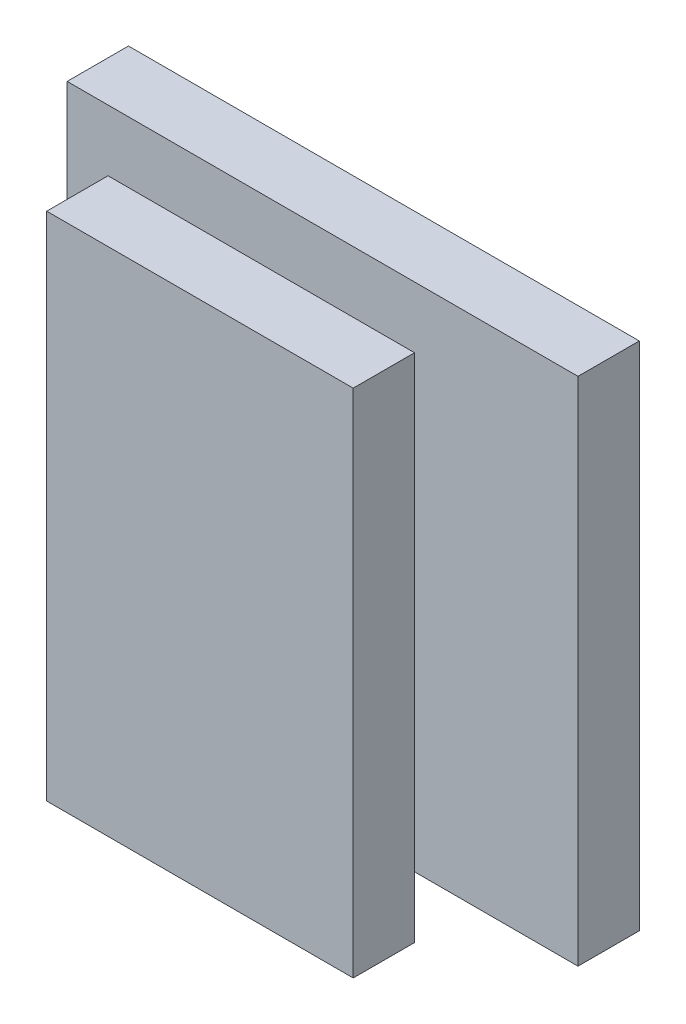
SolidWorks part; units mm, degrees
material "PVC Rigid"
ref_plane "Front Plane" through (0, 0, 0) normal (0, 0, 1) x (1, 0, 0)
ref_plane "Top Plane" through (0, 0, 0) normal (0, 1, 0) x (1, 0, 0)
ref_plane "Right Plane" through (0, 0, 0) normal (1, 0, 0) x (0, 0, -1)
sketch "Sketch2" plane through (0, 0, 0) normal (0, 0, 1) x (1, 0, 0)
  line L2 (-12.5, 12.5) -> (12.5, 12.5)
  line L3 (-12.5, 12.5) -> (-12.5, -12.5)
  line L4 (-12.5, -12.5) -> (12.5, -12.5)
  line L5 (12.5, 12.5) -> (12.5, -12.5)
  point P1 (-12.5, 0)
  point P6 (0, 12.5)
  dimension "D1" = 25
  dimension "D2" = 25
extrude "Boss-Extrude2" add sketch "Sketch2" along normal blind 3
sketch "Sketch3" plane through (0, 0, 3) normal (0, 0, 1) x (1, 0, 0)
  circle A0 centre (0, 0) radius 1.5
extrude "Boss-Extrude3" add sketch "Sketch3" along normal blind 3
sketch "Sketch4" plane through (0, 0, 6) normal (0, 0, 1) x (1, 0, 0)
  line L1 (-7.5, 12.5) -> (7.5, 12.5)
  line L2 (-7.5, 12.5) -> (-7.5, -12.5)
  line L3 (-7.5, -12.5) -> (7.5, -12.5)
  line L4 (7.5, 12.5) -> (7.5, -12.5)
  point P4 (-7.5, 0)
  point P8 (0, 12.5)
  dimension "D1" = 15
  dimension "D2" = 25
extrude "Boss-Extrude4" add sketch "Sketch4" along normal blind 3
